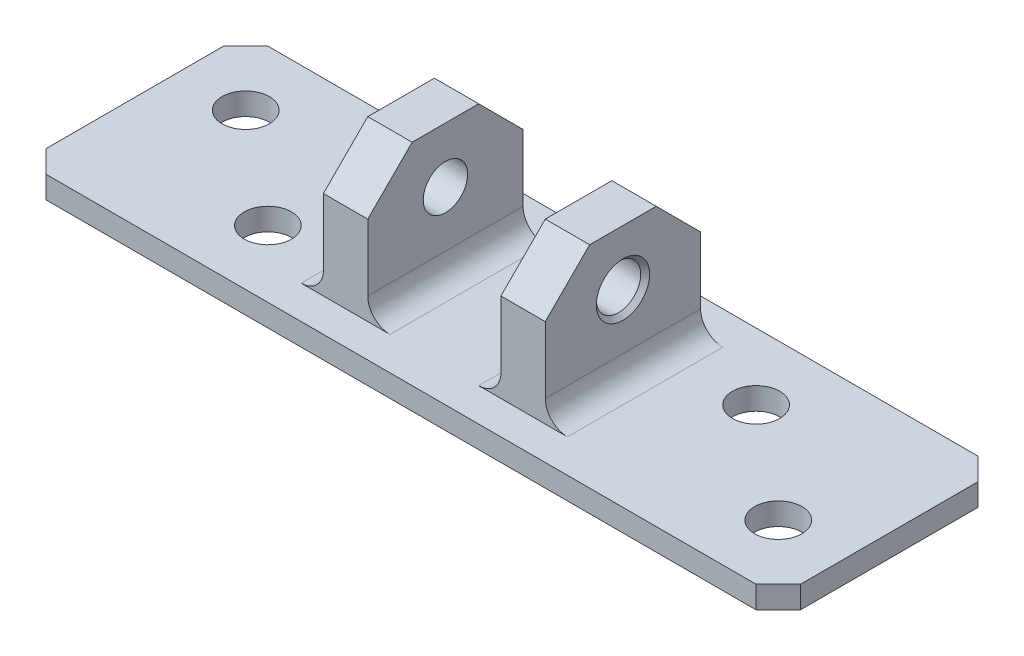
SolidWorks part; units mm, degrees
material "6061 Alloy"
ref_plane "Front Plane" through (0, 0, 0) normal (0, 0, 1) x (1, 0, 0)
ref_plane "Top Plane" through (0, 0, 0) normal (0, 1, 0) x (1, 0, 0)
ref_plane "Right Plane" through (0, 0, 0) normal (1, 0, 0) x (0, 0, -1)
sketch "Sketch1" plane through (0, 0, 0) normal (0, 1, 0) x (1, 0, 0)
  line L1 (53.975, -15.875) -> (-53.975, -15.875)
  line L2 (53.975, -15.875) -> (53.975, 15.875)
  line L3 (53.975, 15.875) -> (-53.975, 15.875)
  line L4 (-53.975, -15.875) -> (-53.975, 15.875)
  line L5 (53.975, -15.875) -> (-53.975, 15.875) construction
  line L6 (53.975, 15.875) -> (-53.975, -15.875) construction
  point P0 (0, 0)
  dimension "D1" = 107.95
  dimension "D2" = 31.75
extrude "Boss-Extrude1" add sketch "Sketch1" along normal mid plane 3.175
hole_wizard "1/4 Clearance Hole1" positions "Sketch2" profile "Sketch3" hole size "1/4" standard "ANSI Inch" end condition up to next
sketch "Sketch2" plane through (0, 1.5875, 0) normal (0, 1, 0) x (1, 0, 0)
  line L0 (0, -1000) -> (0, 49000) construction
  line L1 (-1000, 0) -> (49000, 0) construction
  point P0 (-44.45, 6.35)
  point P19 (28.575, 6.35)
  point P23 (-28.575, -6.35)
  point P25 (44.45, -6.35)
  dimension "D1" = 6.35
  dimension "D2" = 44.45
  dimension "D3" = 28.575
  dimension "D4" = 6.35
  dimension "D5" = 28.575
  dimension "D6" = 44.45
sketch "Sketch3" plane through (-44.45, 1.5875, -6.35) normal (1, 0, 0) x (0, 0, 1)
  line L0 (0, 0) -> (0, 3.175)
  line L1 (0, 3.175) -> (3.3782, 3.175)
  line L2 (3.3782, 3.175) -> (3.3782, 0)
  line L5 (3.3782, 0) -> (0, 0)
  line L11 (0, -6.35) -> (0, 107.95) construction
  dimension "Thru Hole Dia." = 6.7564
  dimension "Thru Hole Depth" = 3.175
sketch "Sketch4" plane through (0, 1.5875, 0) normal (0, 1, 0) x (1, 0, 0)
  line L0 (0, -1000) -> (0, 49000) construction
  line L1 (9.525, 11.1125) -> (15.875, -11.1125) construction
  line L2 (-9.525, -11.1125) -> (-15.875, -11.1125)
  line L3 (-9.525, -11.1125) -> (-9.525, 11.1125)
  line L4 (-9.525, 11.1125) -> (-15.875, 11.1125)
  line L5 (-15.875, -11.1125) -> (-15.875, 11.1125)
  line L6 (-9.525, -11.1125) -> (-15.875, 11.1125) construction
  line L7 (-9.525, 11.1125) -> (-15.875, -11.1125) construction
  line L8 (9.525, -11.1125) -> (15.875, 11.1125) construction
  line L9 (15.875, -11.1125) -> (15.875, 11.1125)
  line L10 (9.525, 11.1125) -> (15.875, 11.1125)
  line L11 (9.525, -11.1125) -> (9.525, 11.1125)
  line L12 (9.525, -11.1125) -> (15.875, -11.1125)
  point P1 (-12.7, 0)
  point P13 (12.7, 0)
  dimension "D1" = 9.525
  dimension "D2" = 6.35
  dimension "D3" = 22.225
extrude "Boss-Extrude2" add sketch "Sketch4" along normal blind 19.05
chamfer "Chamfer2" distance 3.175 angle 45 4 edges at (-53.975, 0, 15.875) (-53.975, 0, -15.875) (53.975, 0, 15.875) (53.975, 0, -15.875)
fillet "Fillet1" radius 3.175 4 edges at (15.875, 1.5875, 0) (9.525, 1.5875, 0) (-9.525, 1.5875, 0) (-15.875, 1.5875, 0)
hole_wizard "1/4 (0.25) Diameter Hole1" positions "Sketch5" profile "Sketch6" hole size "1/4" standard "ANSI Inch" end condition through all
sketch "Sketch5" plane through (15.875, 0, 0) normal (1, 0, 0) x (0, 0, -1)
  line L0 (-12.7, -1.5875) -> (12.7, -1.5875) construction
  point P0 (0, 12.7)
  dimension "D1" = 14.2875
sketch "Sketch6" plane through (15.875, 12.7, 0) normal (0, 1, 0) x (0, 0, -1)
  line L0 (0, 0) -> (0, 31.75)
  line L1 (0, 31.75) -> (3.81, 31.75)
  line L2 (3.175, 31.115) -> (3.175, 0.635)
  line L3 (3.175, 0.635) -> (3.81, 0)
  line L5 (3.81, 0) -> (0, 0)
  line L6 (-3.175, 0.635) -> (-3.81, 0) construction
  line L7 (3.81, 31.75) -> (3.175, 31.115)
  line L8 (-3.81, 31.75) -> (-3.175, 31.115) construction
  line L11 (0, -6.35) -> (0, 107.95) construction
  dimension "Thru Hole Dia." = 6.35
  dimension "Thru Hole Depth" = 31.75
  dimension "Near C'Sink Dia." = 7.62
  dimension "Near C'Sink Angle" = 90
  dimension "Far C'Sink Dia." = 7.62
  dimension "Far C'Sink Angle" = 90
chamfer "Chamfer3" distance 6.35 angle 45 4 edges at (-12.7, 20.6375, -11.1125) (12.7, 20.6375, -11.1125) (12.7, 20.6375, 11.1125) (-12.7, 20.6375, 11.1125)
